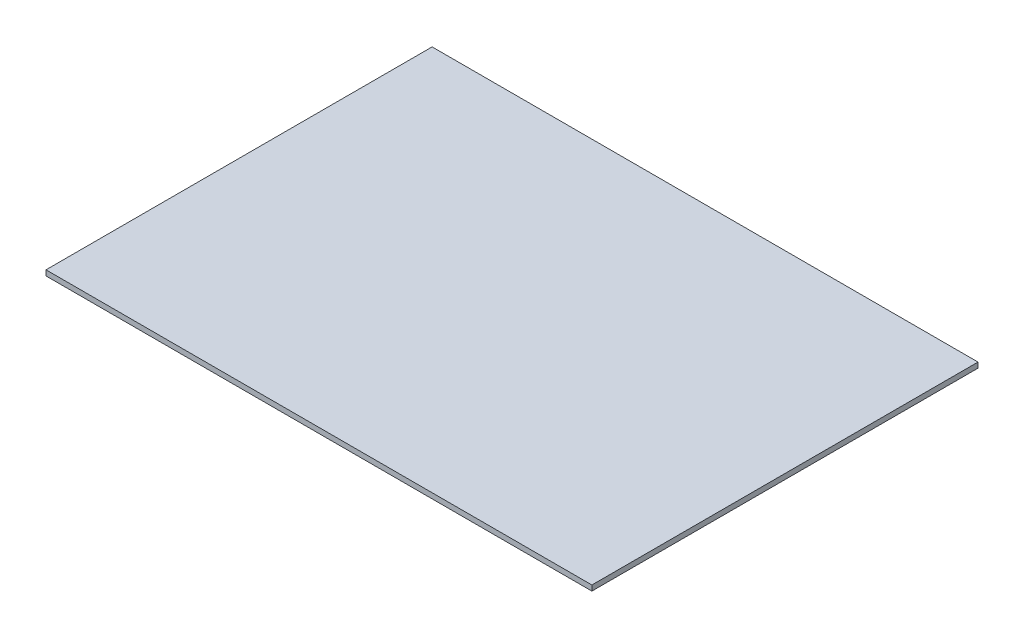
SolidWorks part; units mm, degrees
ref_plane "前视基准面" through (0, 0, 0) normal (0, 0, 1) x (1, 0, 0)
ref_plane "上视基准面" through (0, 0, 0) normal (0, 1, 0) x (1, 0, 0)
ref_plane "右视基准面" through (0, 0, 0) normal (1, 0, 0) x (0, 0, -1)
other "Configuration Table"
sketch "草图1" plane through (0, 0, 0) normal (0, 1, 0) x (1, 0, 0)
  line L1 (-205, 145) -> (205, 145)
  line L2 (-205, 145) -> (-205, -145)
  line L3 (-205, -145) -> (205, -145)
  line L4 (205, 145) -> (205, -145)
  line L5 (-205, 145) -> (205, -145) construction
  line L6 (-205, -145) -> (205, 145) construction
  point P0 (0, 0)
  dimension "D1" = 290
  dimension "D2" = 410
extrude "凸台-拉伸1" add sketch "草图1" along normal blind 4
equation "\"ft\"=5"
